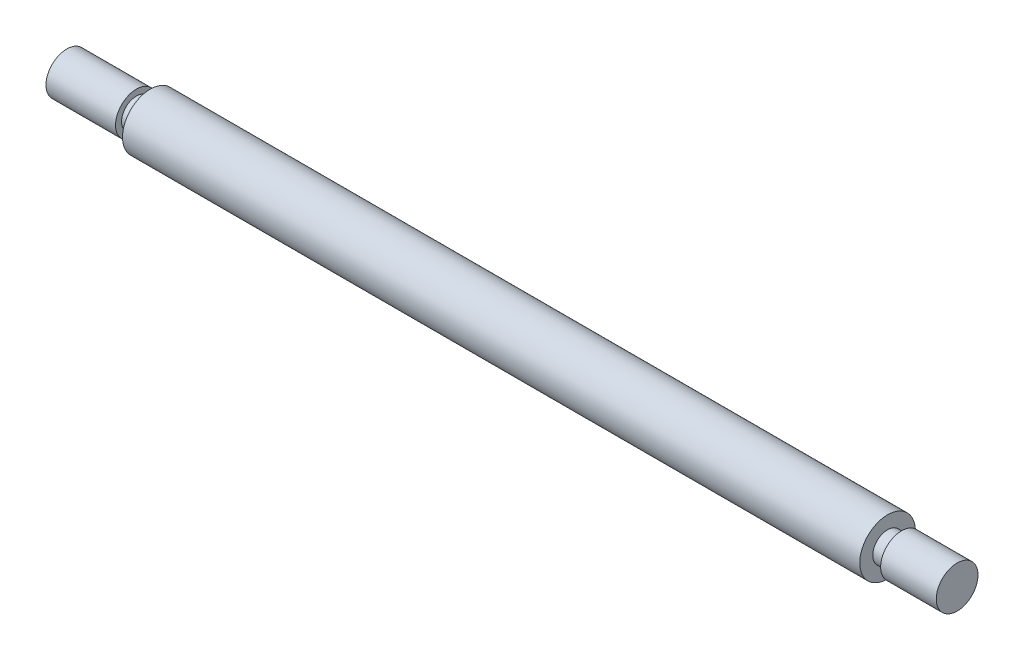
SolidWorks part; units mm, degrees
ref_plane "Alzado" through (0, 0, 0) normal (0, 0, 1) x (1, 0, 0)
ref_plane "Planta" through (0, 0, 0) normal (0, 1, 0) x (1, 0, 0)
ref_plane "Vista lateral" through (0, 0, 0) normal (1, 0, 0) x (0, 0, -1)
sketch "Croquis1" plane through (0, 0, 0) normal (0, 0, 1) x (1, 0, 0)
  line L0 (0, 0) -> (0, 0.1875)
  line L1 (0, 0.1875) -> (0.625, 0.1875)
  line L2 (0.625, 0.1875) -> (0.625, 0.1334)
  line L3 (0.625, 0.1334) -> (0.75, 0.1334)
  line L4 (0.75, 0.1334) -> (0.75, 0.25)
  line L5 (0.75, 0.25) -> (7.375, 0.25)
  line L6 (7.375, 0.25) -> (7.375, 0.1334)
  line L7 (7.375, 0.1334) -> (7.5, 0.1334)
  line L8 (7.5, 0.1334) -> (7.5, 0.1875)
  line L9 (7.5, 0.1875) -> (8, 0.1875)
  line L10 (8, 0.1875) -> (8, 0)
  line L11 (8, 0) -> (0, 0)
  point P8 (1.5468, 0.1044)
  point P14 (0, 0.3088)
  point P15 (6.3512, 0.1837)
  point P16 (7.0975, 0.1532)
  dimension "D1" = 8
  dimension "D2" = 0.25
  dimension "D3" = 0.1334
  dimension "D4" = 0.1875
  dimension "D5" = 0.625
  dimension "D6" = 0.125
  dimension "D7" = 0.1875
  dimension "D8" = 0.5
  dimension "D9" = 0.125
revolve "Revolución1" add sketch "Croquis1" angle 360 about L11
